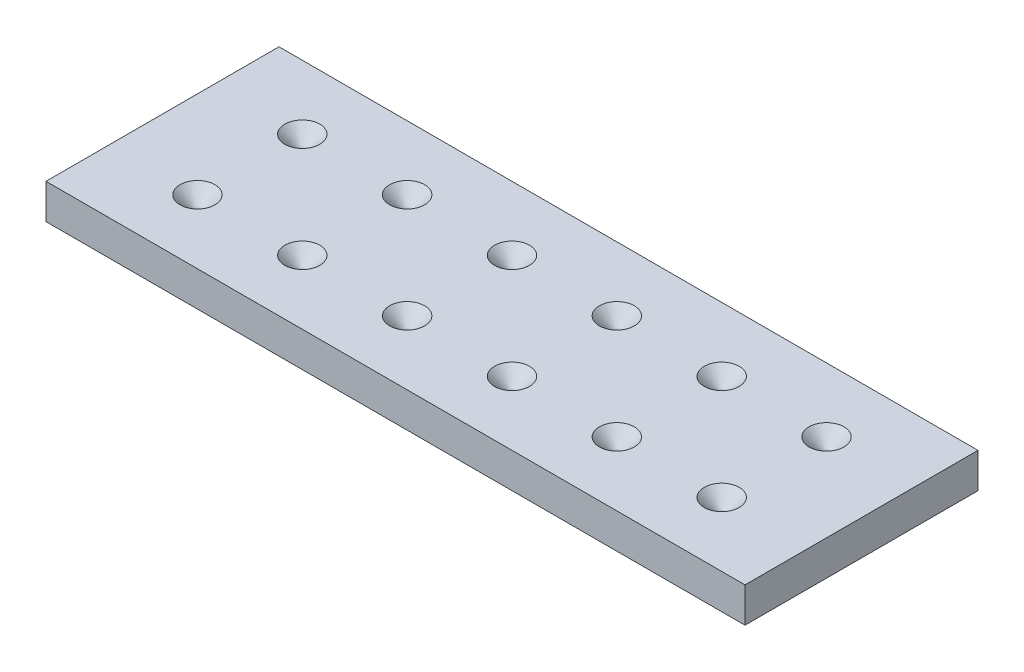
SolidWorks part; units mm, degrees
ref_plane "Front Plane" through (0, 0, 0) normal (0, 0, 1) x (1, 0, 0)
ref_plane "Top Plane" through (0, 0, 0) normal (0, 1, 0) x (1, 0, 0)
ref_plane "Right Plane" through (0, 0, 0) normal (1, 0, 0) x (0, 0, -1)
sketch "Sketch1" plane through (0, 0, 0) normal (0, 1, 0) x (1, 0, 0)
  line L1 (-30, 10) -> (30, 10)
  line L2 (-30, 10) -> (-30, -10)
  line L3 (-30, -10) -> (30, -10)
  line L4 (30, 10) -> (30, -10)
  line L5 (-30, 10) -> (30, -10) construction
  line L6 (-30, -10) -> (30, 10) construction
  point P0 (0, 0)
  dimension "D1" = 60
  dimension "D2" = 20
extrude "Boss-Extrude1" add sketch "Sketch1" along normal blind 3
sketch "Sketch2" plane through (0, 3, 0) normal (0, 1, 0) x (1, 0, 0)
  line L0 (-22.5, -4.5) -> (22.5, -4.5) construction
  line L1 (-30, -4.5) -> (-22.5, -4.5) construction
  line L2 (-30, 10) -> (-30, -10) construction
  line L3 (-22.5, -4.5) -> (-22.5, -10) construction
  line L4 (-30, -10) -> (30, -10) construction
  line L5 (-22.5, -4.5) -> (-22.5, 4.5) construction
  line L6 (-22.5, 4.5) -> (-22.5, 10) construction
  line L7 (30, 10) -> (-30, 10) construction
  line L8 (22.5, -4.5) -> (30, -4.5) construction
  line L9 (30, -10) -> (30, 10) construction
  circle A0 centre (-22.5, -4.5) radius 1.5
  dimension "D3" = 3
  dimension "D1" = 45
  dimension "D2" = 9
extrude "Cut-Extrude1" cut sketch "Sketch2" against normal blind 8 draft 45
pattern_linear "LPattern1" count 6 spacing 9 along (1, 0, 0) count 2 spacing 9 along (0, 0, -1) of "Cut-Extrude1"
